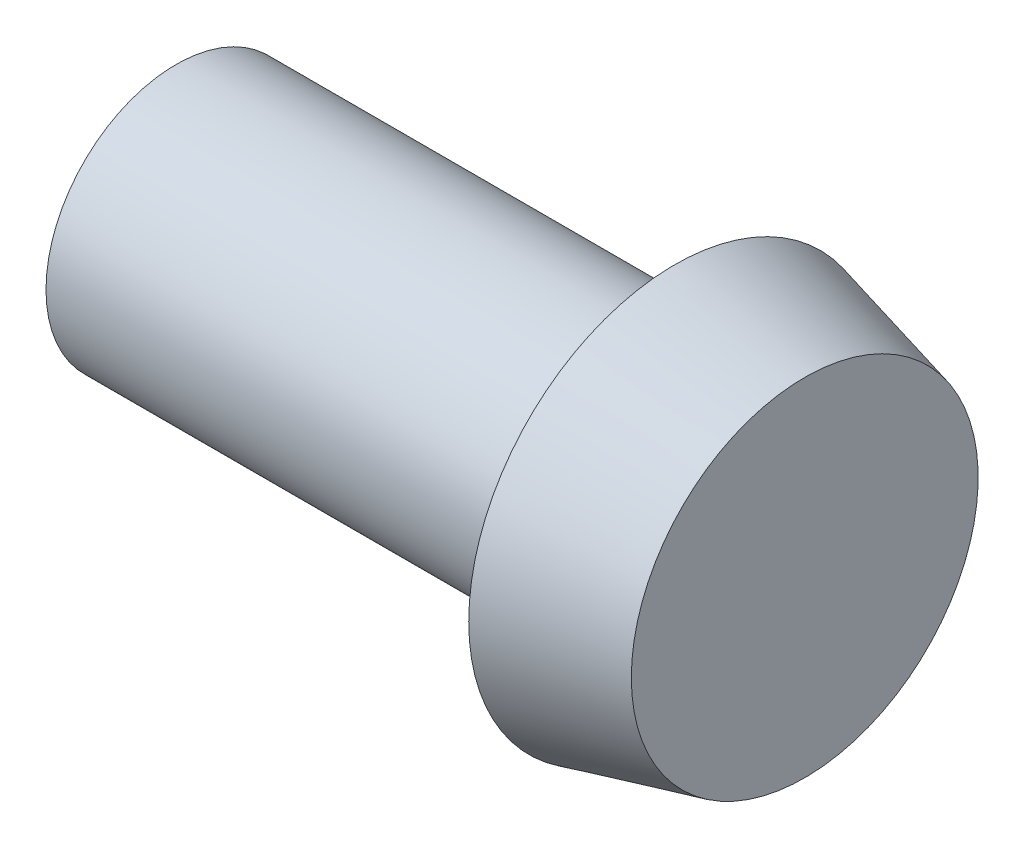
SolidWorks part; units mm, degrees
ref_plane "Front Plane" through (0, 0, 0) normal (0, 0, 1) x (1, 0, 0)
ref_plane "Top Plane" through (0, 0, 0) normal (0, 1, 0) x (1, 0, 0)
ref_plane "Right Plane" through (0, 0, 0) normal (1, 0, 0) x (0, 0, -1)
sketch "Sketch5" plane through (0, 0, 0) normal (0, 1, 0) x (1, 0, 0)
  line L4 (-30.465, 0) -> (22.1993, 0) construction
  line L12 (0, 6) -> (-23, 6)
  line L13 (0, 0) -> (6, 0)
  line L14 (6, 0) -> (6, 8)
  line L15 (0, 9.5) -> (6, 8)
  line L16 (0, 6) -> (0, 9.5)
  line L17 (-23, 6) -> (-23, 0)
  line L18 (-23, 0) -> (6, 0)
  point P7 (0, 0)
  dimension "D1" = 29
  dimension "D2" = 23
  dimension "D3" = 6
  dimension "D4" = 9.5
  dimension "D5" = 8
  dimension "D6" = 6
revolve "Revolve2" add sketch "Sketch5" angle 360 about L4
